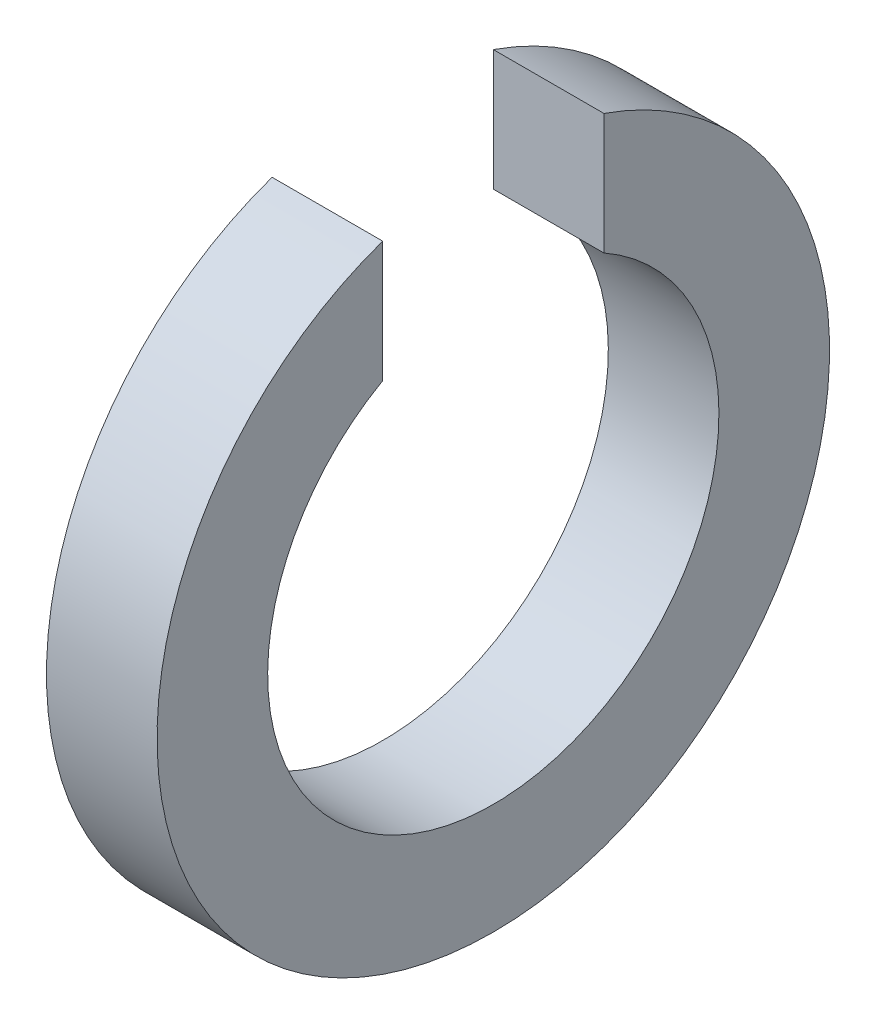
SolidWorks part; units mm, degrees
ref_plane "Front Plane" through (0, 0, 0) normal (0, 0, 1) x (1, 0, 0)
ref_plane "Top Plane" through (0, 0, 0) normal (0, 1, 0) x (1, 0, 0)
ref_plane "Right Plane" through (0, 0, 0) normal (1, 0, 0) x (0, 0, -1)
sketch "Sketch1" plane through (0, 0, 0) normal (0, 0, 1) x (1, 0, 0)
  line L0 (0, 0) -> (23.0517, 0) construction
  line L1 (1.25, 5.1) -> (-1.25, 5.1)
  line L2 (1.25, 5.1) -> (1.25, 7.6)
  line L3 (1.25, 7.6) -> (-1.25, 7.6)
  line L4 (-1.25, 5.1) -> (-1.25, 7.6)
  line L5 (1.25, 5.1) -> (-1.25, 7.6) construction
  line L6 (1.25, 7.6) -> (-1.25, 5.1) construction
  point P0 (0, 6.35)
  dimension "D1" = 5.1
  dimension "D2" = 7.6
  dimension "D3" = 2.5
revolve "Revolve1" add sketch "Sketch1" angle 360 about L0
sketch "Sketch2" plane through (1.25, 0, 0) normal (1, 0, 0) x (0, 0, -1)
  line L0 (0, 0) -> (0, 7.6) construction
  line L1 (-2.5, 7.177) -> (-2.5, 4.4452)
  line L2 (2.5, 7.177) -> (2.5, 4.4452)
  circle A0 centre (0, 0) radius 7.6 construction
  circle A1 centre (0, 0) radius 5.1 construction
  arc A2 (2.5, 4.4452) -> (-2.5, 4.4452) centre (0, 0) ccw
  arc A3 (2.5, 7.177) -> (-2.5, 7.177) centre (0, 0) ccw
  dimension "D1" = 2.5
extrude "Cut-Extrude1" cut sketch "Sketch2" against normal up to next
